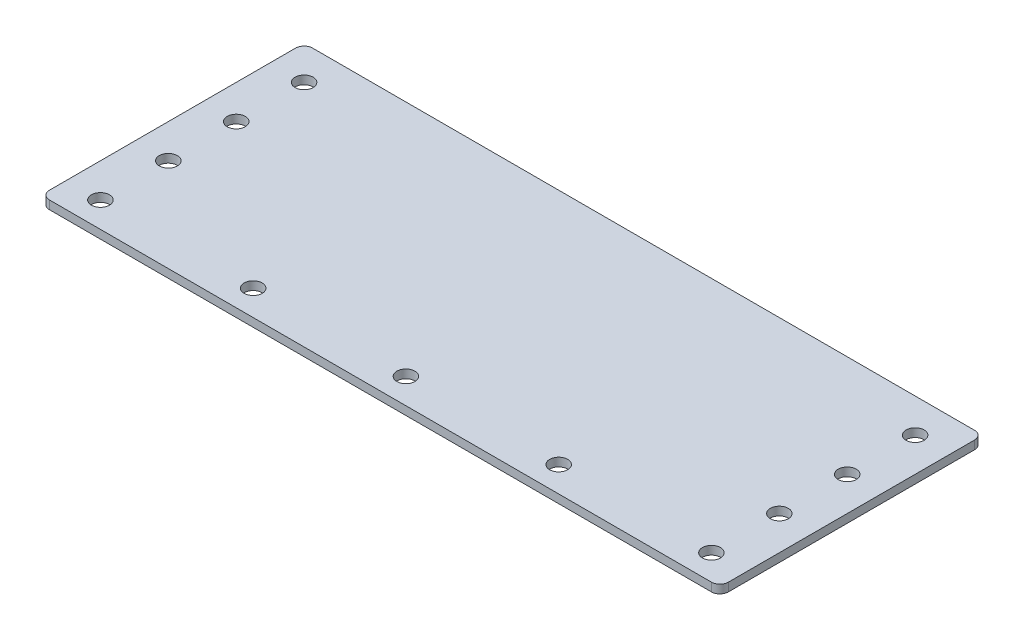
SolidWorks part; units mm, degrees
ref_plane "Front Plane" through (0, 0, 0) normal (0, 0, 1) x (1, 0, 0)
ref_plane "Top Plane" through (0, 0, 0) normal (0, 1, 0) x (1, 0, 0)
ref_plane "Right Plane" through (0, 0, 0) normal (1, 0, 0) x (0, 0, -1)
sketch "Sketch1" plane through (0, 0, 0) normal (0, 1, 0) x (1, 0, 0)
  line L0 (0, 0) -> (0, 93.7312) construction
  line L1 (-127, -49.2125) -> (127, -49.2125)
  line L2 (-127, -49.2125) -> (-127, 49.2125)
  line L3 (-127, 49.2125) -> (127, 49.2125)
  line L4 (127, -49.2125) -> (127, 49.2125)
  line L5 (-127, -49.2125) -> (127, 49.2125) construction
  line L6 (-127, 49.2125) -> (127, -49.2125) construction
  circle A0 centre (-114.3, 36.5125) radius 6.35 construction
  circle A1 centre (-114.3, 11.1125) radius 6.35 construction
  circle A2 centre (-114.3, -14.2875) radius 6.35 construction
  circle A3 centre (57.15, -39.6875) radius 6.35 construction
  circle A4 centre (-57.15, -39.6875) radius 6.35 construction
  circle A5 centre (0, -39.6875) radius 6.35 construction
  circle A6 centre (114.3, -14.2875) radius 6.35 construction
  circle A7 centre (114.3, 11.1125) radius 6.35 construction
  circle A8 centre (114.3, 36.5125) radius 6.35 construction
  circle A9 centre (-114.3, -39.6875) radius 6.35 construction
  circle A10 centre (114.3, -39.6875) radius 6.35 construction
  point P0 (0, 0)
  point P17 (-114.3, 11.1125)
  point P38 (-114.3, -14.2875)
  point P39 (-114.3, -14.2875)
  point P42 (-57.15, -39.6875)
  point P47 (-114.3, 36.5125)
  dimension "D3" = 12.7
  dimension "D1" = 254
  dimension "D2" = 98.425
  dimension "D4" = 12.7
  dimension "D5" = 12.7
  dimension "D9" = 57.15
  dimension "D7" = 57.15
  dimension "D8" = 25.4
  dimension "D6" = 4
extrude "Boss-Extrude1" add sketch "Sketch1" along normal blind 3.175 contours L2 A0 L1 L4 L3 | A0
hole_wizard "Tap Drill for 1/4 Helicoil2" positions "Sketch2" profile "Sketch3" hole size "1/4-20" standard "ANSI Inch" end condition through all
sketch "Sketch2" plane through (0, 0, 0) normal (0, -1, 0) x (-1, 0, 0)
  point P0 (-114.3, 36.5125)
  point P3 (-114.3, 11.1125)
  point P6 (-114.3, -14.2875)
  point P9 (-57.15, -39.6875)
  point P12 (0, -39.6875)
  point P15 (57.15, -39.6875)
  point P18 (114.3, -14.2875)
  point P21 (114.3, 11.1125)
  point P24 (114.3, 36.5125)
  point P27 (114.3, -39.6875)
  point P30 (-114.3, -39.6875)
sketch "Sketch3" plane through (114.3, 0, -36.5125) normal (1, 0, 0) x (0, 0, -1)
  line L0 (0, 0) -> (0, 3.175)
  line L1 (0, 3.175) -> (3.3782, 3.175)
  line L2 (3.3782, 3.175) -> (3.3782, 0)
  line L5 (3.3782, 0) -> (0, 0)
  line L11 (0, -6.35) -> (0, 107.95) construction
  dimension "Thru Hole Dia." = 6.7564
  dimension "Thru Hole Depth" = 3.175
fillet "Fillet1" radius 3.175 4 edges at (127, 1.5875, -49.2125) (-127, 1.5875, -49.2125) (-127, 1.5875, 49.2125) (127, 1.5875, 49.2125)
sketch "Sketch4" [suppressed] plane through (0, 3.175, 0) normal (0, 1, 0) x (1, 0, 0)
  line L0 (0, 0) -> (0, 93.7312) construction
  line L1 (0, 0) -> (0, 93.7312)
  line L2 (-127, 49.2125) -> (127, 49.2125) construction
  point P2 (0, 39.6875)
  point P3 (0, 14.2875)
  dimension "D1" = 9.525
  dimension "D2" = 25.4
hole_wizard "Tap Drill for #8 Helicoil1" [suppressed] positions "Sketch5" profile "Sketch6" hole size "#8-32" standard "ANSI Inch"
sketch "Sketch5" plane through (0, 3.175, 0) normal (0, 1, 0) x (1, 0, 0)
  point P0 (0, 39.6875)
  point P3 (0, 14.2875)
sketch "Sketch6" plane through (0, 3.175, -39.6875) normal (1, 0, 0) x (0, 0, 1)
  line L0 (0, 0) -> (0, 3.175)
  line L1 (0, 3.175) -> (2.1971, 3.175)
  line L2 (2.1971, 3.175) -> (2.1971, 0)
  line L5 (2.1971, 0) -> (0, 0)
  line L11 (0, -6.35) -> (0, 107.95) construction
  dimension "Thru Hole Dia." = 4.3942
  dimension "Thru Hole Depth" = 3.175
